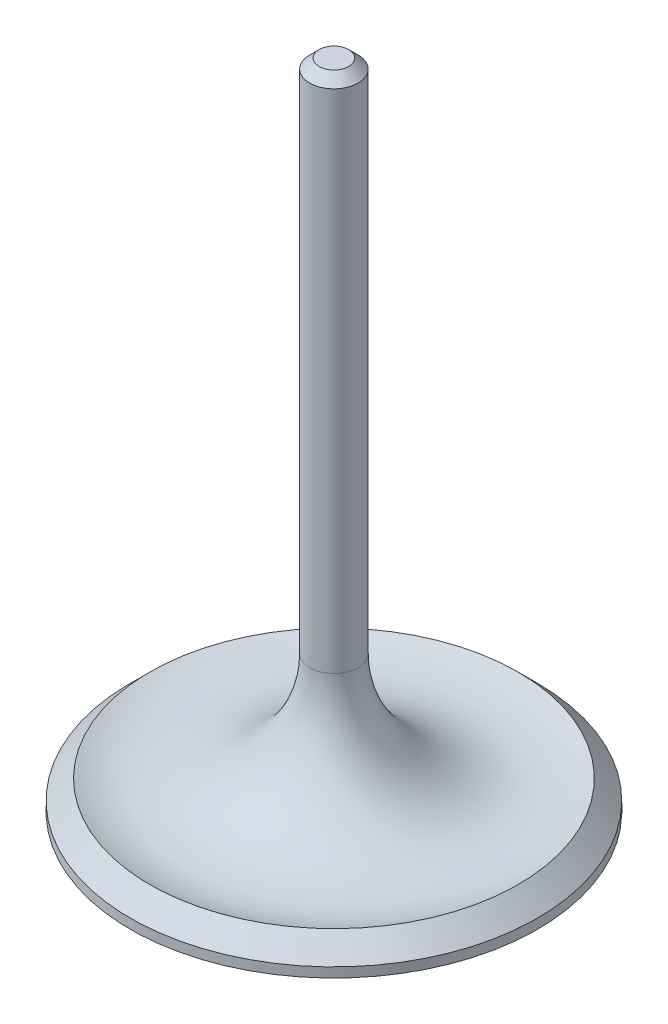
SolidWorks part; units mm, degrees
ref_plane "Front Plane" through (0, 0, 0) normal (0, 0, 1) x (1, 0, 0)
ref_plane "Top Plane" through (0, 0, 0) normal (0, 1, 0) x (1, 0, 0)
ref_plane "Right Plane" through (0, 0, 0) normal (1, 0, 0) x (0, 0, -1)
sketch "Sketch1" plane through (0, 0, 0) normal (1, 0, 0) x (0, 0, -1)
  line L0 (0, 0) -> (0, 85.55)
  line L1 (0, 85.55) -> (3.18, 85.55)
  line L2 (3.18, 85.55) -> (3.18, 17.9547)
  line L3 (24.13, 3.81) -> (26.67, 1.27)
  line L4 (26.67, 1.27) -> (26.67, 0)
  line L5 (26.67, 0) -> (0, 0)
  arc A0 (3.18, 17.9547) -> (24.13, 3.81) centre (18.43, 17.9547) ccw
  point P7 (7.1176, 85.55)
  dimension "D7" = 15.25
  dimension "D1" = 85.55
  dimension "D2" = 26.67
  dimension "D3" = 1.27
  dimension "D4" = 3.81
  dimension "D5" = 45
  dimension "D6" = 3.18
revolve "Revolve1" add sketch "Sketch1" angle 360 about L0
chamfer "Chamfer1" distance 1.25 angle 45 1 edges at (0, 85.55, -3.18)
